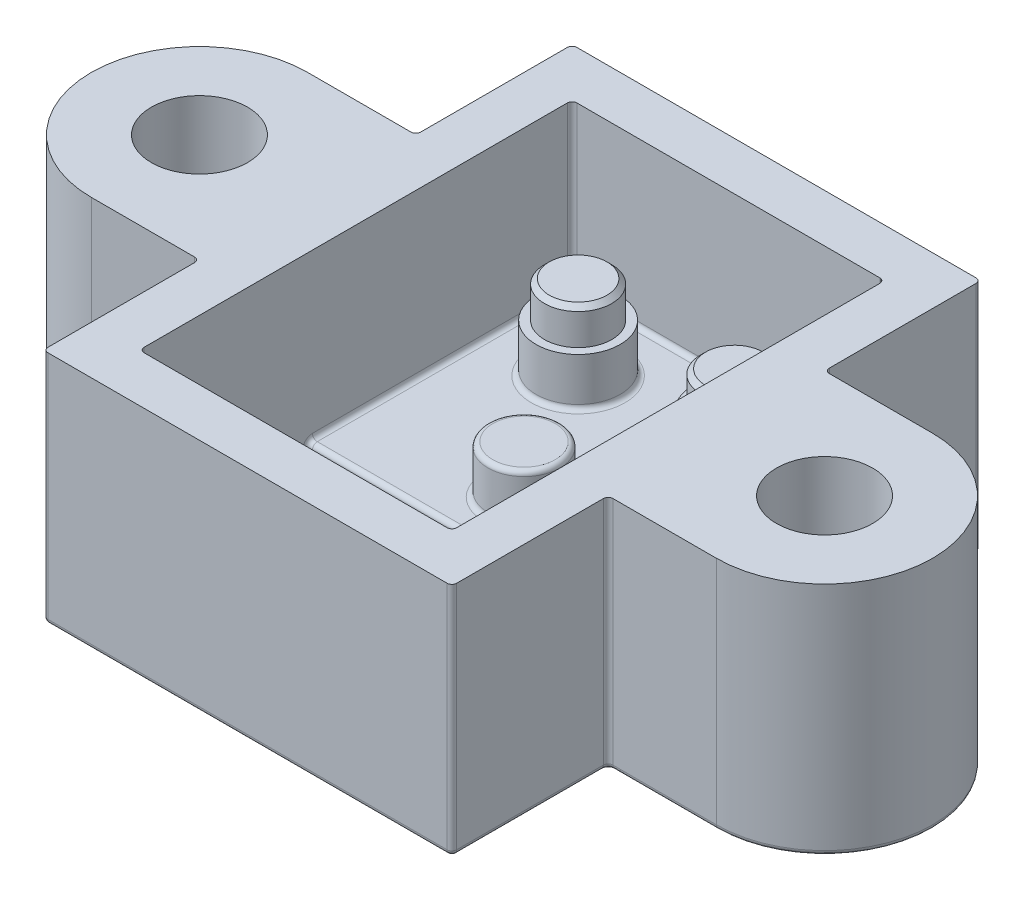
SolidWorks part; units mm, degrees
ref_plane "Front Plane" through (0, 0, 0) normal (0, 0, 1) x (1, 0, 0)
ref_plane "Top Plane" through (0, 0, 0) normal (0, 1, 0) x (1, 0, 0)
ref_plane "Right Plane" through (0, 0, 0) normal (1, 0, 0) x (0, 0, -1)
sketch "Sketch1" plane through (0, 0, 0) normal (0, 1, 0) x (1, 0, 0)
  line L0 (-8.5, -11) -> (-8.5, 11)
  line L1 (-6.5, -9) -> (6.5, -9)
  line L2 (-6.5, -9) -> (-6.5, 9)
  line L3 (-6.5, 9) -> (6.5, 9)
  line L4 (6.5, -9) -> (6.5, 9)
  line L5 (-6.5, -9) -> (6.5, 9) construction
  line L6 (-6.5, 9) -> (6.5, -9) construction
  line L7 (-8.5, 11) -> (8.5, 11)
  line L8 (8.5, -11) -> (8.5, 11)
  line L9 (-8.5, -11) -> (8.5, -11)
  point P0 (0, 0)
  dimension "D1" = 13
  dimension "D2" = 18
  dimension "D3" = 2
extrude "Boss-Extrude1" add sketch "Sketch1" along normal blind 6.8
sketch "Sketch2" plane through (0, 0, 0) normal (0, -1, 0) x (1, 0, 0)
  line L1 (-8.5, 11) -> (8.5, 11)
  line L2 (-8.5, 11) -> (-8.5, -11)
  line L3 (-8.5, -11) -> (8.5, -11)
  line L4 (8.5, 11) -> (8.5, -11)
extrude "Boss-Extrude2" add sketch "Sketch2" along normal blind 3
sketch "Sketch3" plane through (0, 0, 0) normal (0, 1, 0) x (1, 0, 0)
  line L0 (-3.25, 6) -> (3.25, 6) construction
  point P4 (0, 6)
  dimension "D2" = 6
  dimension "D1" = 6.5
ref_plane "Plane1" through (0, 0, -6) normal (0, 0, 1) x (1, 0, 0)
sketch "Sketch4" plane through (0, 0, -6) normal (0, 0, 1) x (1, 0, 0)
  line L0 (-3.25, 0) -> (-3.25, 3.5)
  line L1 (-3.25, 0) -> (3.25, 0) construction
  line L2 (-3.25, 3.5) -> (-4.45, 3.5)
  line L3 (-4.65, 3.3) -> (-4.65, 2)
  line L4 (-4.65, 2) -> (-5, 2)
  line L5 (-5, 2) -> (-5, 0)
  line L6 (-5, 0) -> (-3.25, 0)
  line L7 (-4.45, 3.5) -> (-4.65, 3.3)
  point P4 (-4.65, 3.5)
  dimension "D1" = 1.75
  dimension "D2" = 2
  dimension "D3" = 3.5
  dimension "D4" = 1.4
revolve "Revolve1" add sketch "Sketch4" angle 360 about L0
mirror "Mirror1" about plane through (0, 0, 0) normal (1, 0, 0) of "Revolve1"
sketch "Sketch5" plane through (0, 0, 0) normal (0, 1, 0) x (1, 0, 0)
  line L0 (-6.5, -9) -> (6.5, -9) construction
  line L1 (-6.5, -2) -> (6.5, -2)
  line L2 (-6.5, -2) -> (-6.5, -9)
  line L3 (-6.5, -9) -> (6.5, -9)
  line L4 (6.5, -2) -> (6.5, -9)
  line L5 (-6.5, -2) -> (6.5, -9) construction
  line L6 (-6.5, -9) -> (6.5, -2) construction
  line L7 (6.5, -9) -> (6.5, 9) construction
  point P0 (0, -5.5)
  dimension "D1" = 2
extrude "Cut-Extrude1" cut sketch "Sketch5" against normal through all
sketch "Sketch6" plane through (0, 0, 0) normal (0, 1, 0) x (1, 0, 0)
  line L0 (0, 0) -> (0, 0.5) construction
  circle A0 centre (0, 0.5) radius 1.5
  dimension "D1" = 3
  dimension "D2" = 0.5
extrude "Boss-Extrude3" add sketch "Sketch6" along normal blind 2
sketch "Sketch7" plane through (0, -3, 0) normal (0, -1, 0) x (1, 0, 0)
  line L0 (-13, 0) -> (-8.5, 0) construction
  line L1 (-8.5, 11) -> (-8.5, -11) construction
  line L2 (-8.5, 4.5) -> (-13, 4.5)
  line L3 (-8.5, -4.5) -> (-13, -4.5)
  line L4 (-8.5, 4.5) -> (-8.5, -4.5)
  circle A0 centre (-13, 0) radius 2
  arc A1 (-13, 4.5) -> (-13, -4.5) centre (-13, 0) ccw
  arc A2 (-13, 4.5) -> (-13, -4.5) centre (-13, 0) cw construction
  dimension "D1" = 4
  dimension "D2" = 2.5
extrude "Boss-Extrude4" add sketch "Sketch7" against normal up to surface (9.8 mm away) up to face at (0, 6.8, 0)
mirror "Mirror2" about plane through (0, 0, 0) normal (1, 0, 0) of "Boss-Extrude4"
chamfer "Chamfer1" distance 2 angle 45 2 edges at (-13, -3, -2) (13, -3, -2)
fillet "Fillet1" radius 0.2 40 edges at (13, -3, -4) (-13, -3, -4) (6.5, 1.9, 9) (0, 0, -9) (6.5, 3.4, -9) (-6.5, 0, -3.5) (-6.5, 3.4, -9) (-6.5, 1.9, 9) (-8.5, -3, 7.75) (0, -3, -11) (8.5, -3, -7.75) (0, -3, 11) (-3.25, 0, -7.75) (3.25, 0, -7.75) (6.5, 0, -3.5) (6.5, -3, 5.5) (6.5, -1.5, 2) (0, -3, 9) (-6.5, -3, 5.5) (0, -3, 2) (-6.5, -1.5, 2) (0, 0, 2) (0, 0, -2) (0, 2, 1) (-8.5, 1.9, 11) (-8.5, 1.9, -11) (8.5, 1.9, -11) (-8.5, -3, -7.75) (8.5, 1.9, 11) (-8.5, 1.9, 4.5) (-8.5, 1.9, -4.5) (-10.75, -3, 4.5) (-17.5, -3, 0) (-10.75, -3, -4.5) (8.5, -3, 7.75) (10.75, -3, -4.5) (17.5, -3, 0) (8.5, 1.9, 4.5) (10.75, -3, 4.5) (8.5, 1.9, -4.5)
